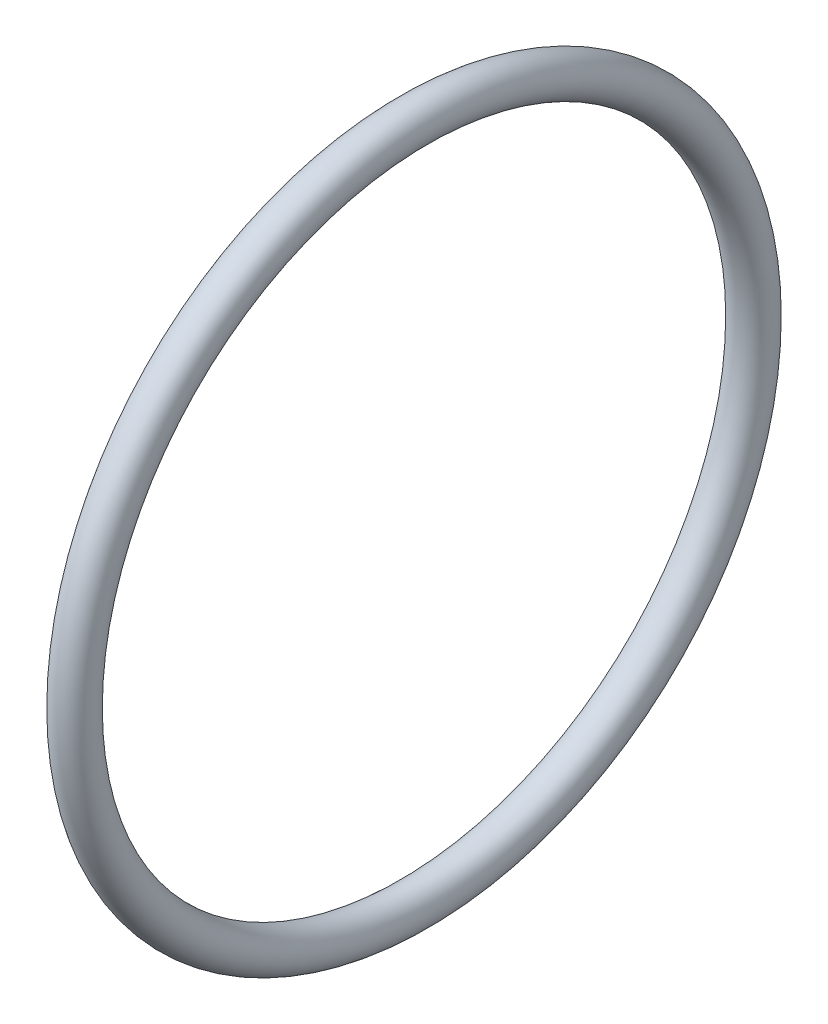
SolidWorks part; units mm, degrees
ref_plane "Front Plane" through (0, 0, 0) normal (0, 0, 1) x (1, 0, 0)
ref_plane "Top Plane" through (0, 0, 0) normal (0, 1, 0) x (1, 0, 0)
ref_plane "Right Plane" through (0, 0, 0) normal (1, 0, 0) x (0, 0, -1)
sketch "Sketch1" plane through (0, 0, 0) normal (0, 0, 1) x (1, 0, 0)
  line L0 (0, 0) -> (27.1095, 0) construction
  line L1 (0, 0) -> (0, 17.275) construction
  circle A0 centre (0, 17.275) radius 1
  point P5 (0, 16.275)
  point P6 (1, 17.275)
  point P7 (0, 18.275)
  point P8 (-1, 17.275)
  dimension "D1" = 17.275
  dimension "D2" = 2
revolve "Revolve1" add sketch "Sketch1" angle 360 about L0
